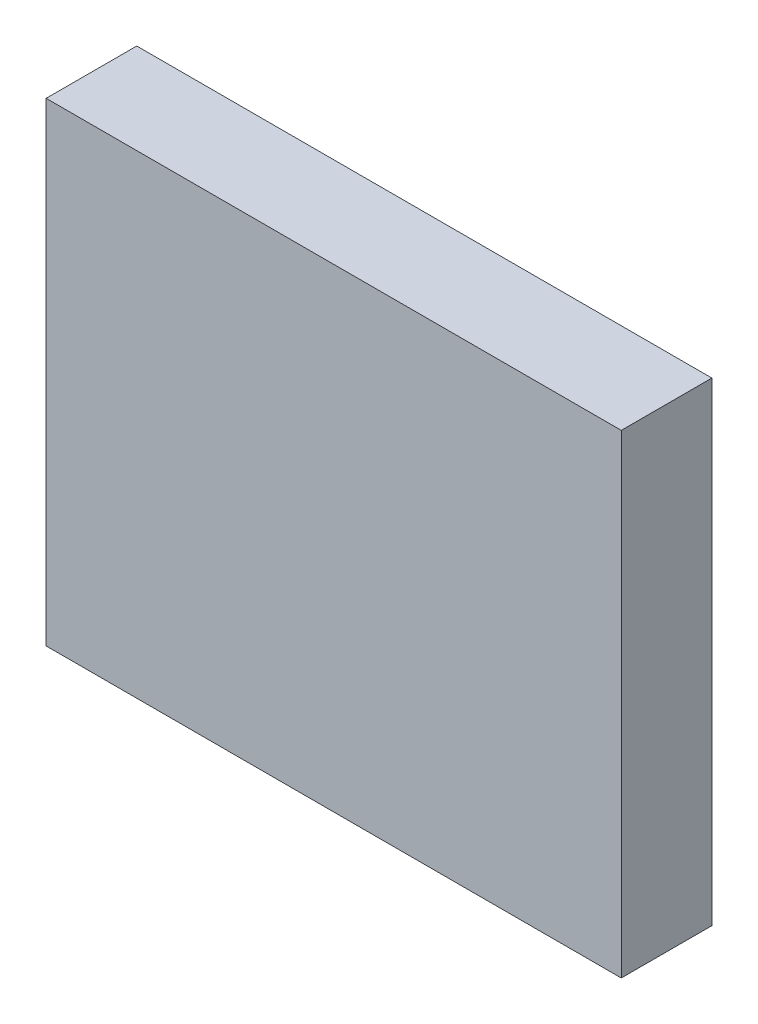
SolidWorks part; units mm, degrees
ref_plane "Front" through (0, 0, 0) normal (0, 0, 1) x (1, 0, 0)
ref_plane "Top" through (0, 0, 0) normal (0, 1, 0) x (1, 0, 0)
ref_plane "Right" through (0, 0, 0) normal (1, 0, 0) x (0, 0, -1)
sketch "Sketch4" plane through (0, 0, 0) normal (0, 1, 0) x (1, 0, 0)
  line L1 (0, 0) -> (-15.7641, 0)
  line L2 (0, 0) -> (0, 2.4834)
  line L3 (0, 2.4834) -> (-15.7641, 2.4834)
  line L4 (-15.7641, 0) -> (-15.7641, 2.4834)
extrude "Boss-Extrude1" add sketch "Sketch4" along normal blind 13
